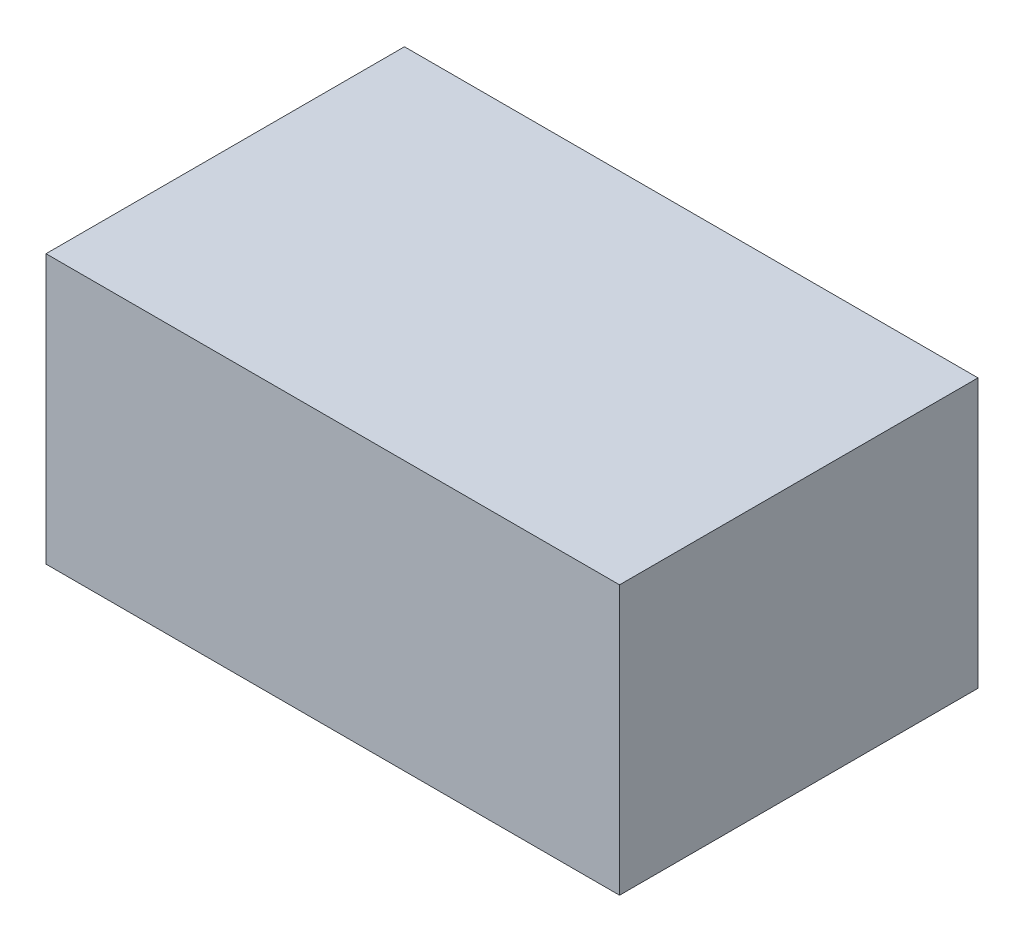
SolidWorks part; units mm, degrees
ref_plane "前视" through (0, 0, 0) normal (0, 0, 1) x (1, 0, 0)
ref_plane "上视" through (0, 0, 0) normal (0, 1, 0) x (1, 0, 0)
ref_plane "右视" through (0, 0, 0) normal (1, 0, 0) x (0, 0, -1)
sketch "Sketch1" plane through (0, 0, 0) normal (0, 1, 0) x (1, 0, 0)
  line L1 (-109.8305, 94.2373) -> (210.1695, 94.2373)
  line L2 (-109.8305, 94.2373) -> (-109.8305, -105.7627)
  line L3 (-109.8305, -105.7627) -> (210.1695, -105.7627)
  line L4 (210.1695, 94.2373) -> (210.1695, -105.7627)
  dimension "D1" = 320
  dimension "D2" = 200
extrude "Boss-Extrude1" add sketch "Sketch1" along normal blind 150
shell "Shell2" thickness 3
sketch "Sketch2" plane through (0, 150, 0) normal (0, 1, 0) x (1, 0, 0)
  line L1 (-147.7858, 136.6973) -> (237.2266, 136.6973)
  line L2 (-147.7858, 136.6973) -> (-147.7858, -129.2198)
  line L3 (-147.7858, -129.2198) -> (237.2266, -129.2198)
  line L4 (237.2266, 136.6973) -> (237.2266, -129.2198)
